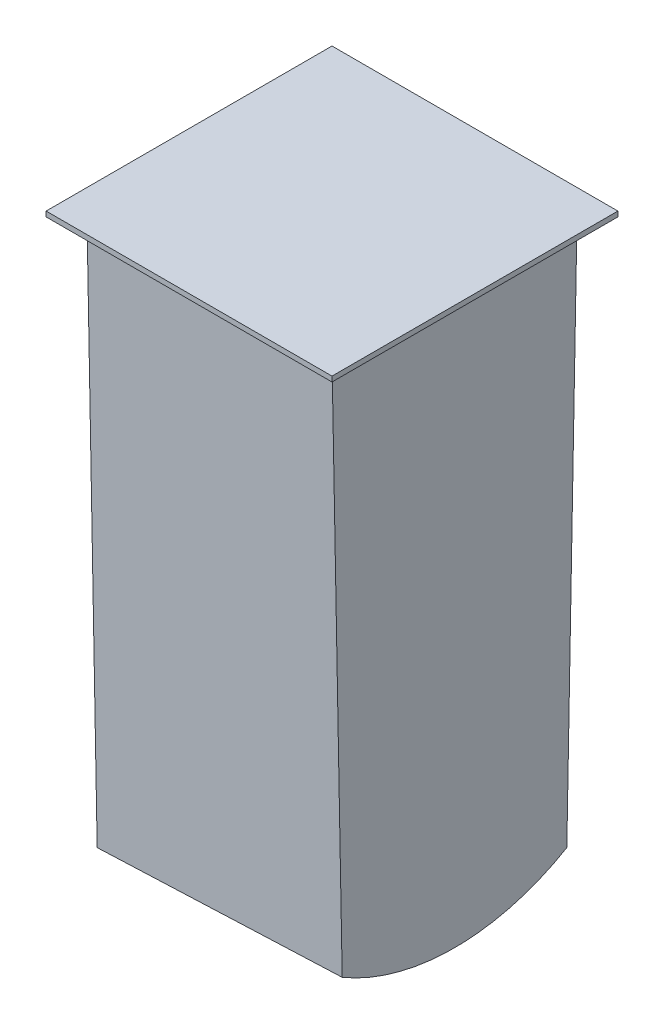
SolidWorks part; units mm, degrees
ref_plane "Front Plane" through (0, 0, 0) normal (0, 0, 1) x (1, 0, 0)
ref_plane "Top Plane" through (0, 0, 0) normal (0, 1, 0) x (1, 0, 0)
ref_plane "Right Plane" through (0, 0, 0) normal (1, 0, 0) x (0, 0, -1)
sketch3d "3DSketch2" plane through (0, 0, 0) normal (0, 0, 1) x (1, 0, 0)
sketch "Tall side" plane through (0, 0, 0) normal (1, 0, 0) x (0, 0, -1)
  line L0 (640.7123, 692.6446) -> (335.9123, 692.6446)
  line L1 (335.9123, 692.6446) -> (348.6123, 6.8446)
  line L2 (348.6123, 6.8446) -> (628.0123, 6.8446) construction
  line L3 (628.0123, 6.8446) -> (640.7123, 692.6446)
  line L4 (488.3123, 692.6446) -> (488.3123, -43.9554) construction
  arc A0 (628.0123, 6.8446) -> (348.6123, 6.8446) centre (488.3123, 173.5321) cw
  point P2 (488.3123, -43.9554)
  point P6 (488.3123, 692.6446)
  dimension "D1" = 50.8
  dimension "D2" = 279.4
  dimension "D3" = 304.8
  dimension "D4" = 736.6
sketch "Short side" plane through (304.8, 0, 0) normal (1, 0, 0) x (0, 0, -1)
  line L0 (640.7163, 692.6446) -> (335.9163, 692.6446)
  line L1 (335.9163, 692.6446) -> (348.6163, 19.5446)
  line L2 (348.6163, 19.5446) -> (628.0163, 19.5446) construction
  line L3 (628.0163, 19.5446) -> (640.7163, 692.6446)
  line L5 (488.3163, 692.6446) -> (488.3163, -18.5554) construction
  arc A0 (628.0163, 19.5446) -> (348.6163, 19.5446) centre (488.3163, 256.6112) cw
  point P6 (488.3163, 692.6446)
  dimension "D1" = 673.1
  dimension "D2" = 279.4
  dimension "D3" = 304.8
  dimension "D4" = 38.1
loft "Body" add profiles "Tall side", "Short side"
sketch "Sketch9" plane through (0, 692.6446, 0) normal (0, 1, 0) x (1, 0, 0)
  line L0 (0, 640.7123) -> (0, 335.9123) construction
  line L1 (-25.4, 666.1143) -> (330.2, 666.1143)
  line L2 (-25.4, 666.1143) -> (-25.4, 310.5143)
  line L3 (-25.4, 310.5143) -> (330.2, 310.5143)
  line L4 (330.2, 666.1143) -> (330.2, 310.5143)
  line L7 (304.8, 640.7163) -> (304.8, 335.9163) construction
  line L8 (0, 335.9123) -> (304.8, 335.9163) construction
  line L9 (0, 640.7123) -> (304.8, 640.7163) construction
  point P10 (152.4, 335.9143)
  point P11 (152.4, 640.7143)
  dimension "D1" = 25.4
  dimension "D2" = 25.4
  dimension "D3" = 25.4
  dimension "D4" = 25.4
extrude "Lid" add sketch "Sketch9" along normal blind 6.35
